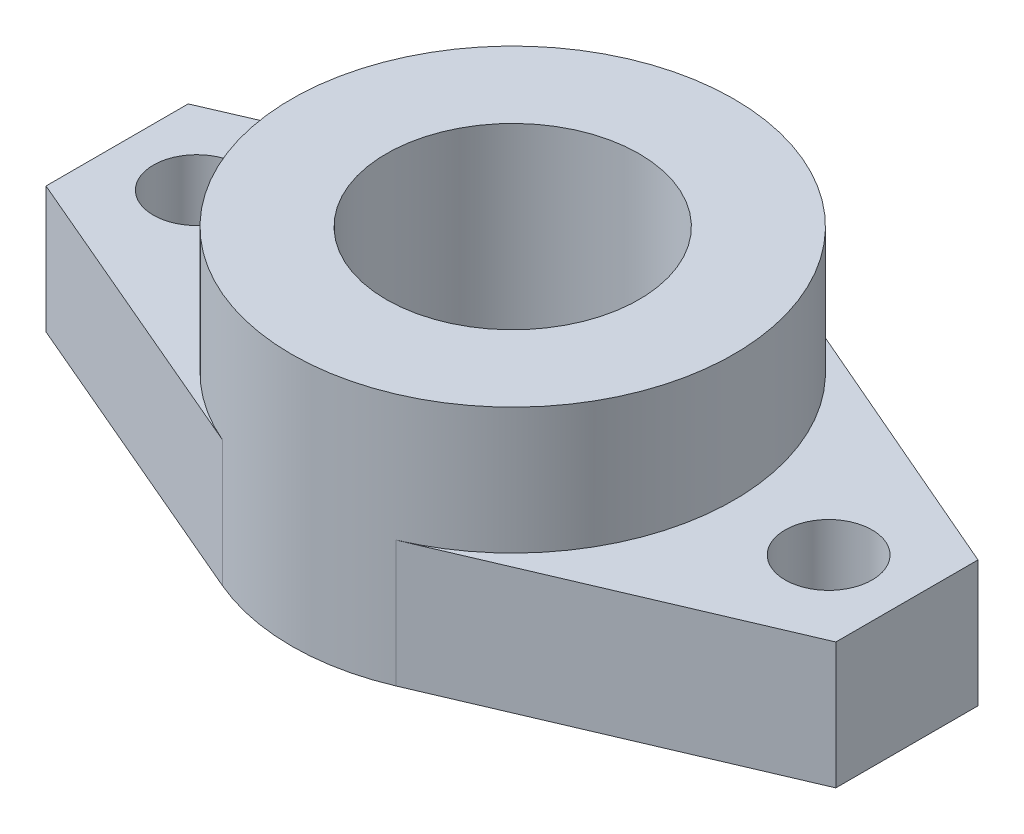
SolidWorks part; units mm, degrees
material "1060 合金"
ref_plane "前视基准面" through (0, 0, 0) normal (0, 0, 1) x (1, 0, 0)
ref_plane "上视基准面" through (0, 0, 0) normal (0, 1, 0) x (1, 0, 0)
ref_plane "右视基准面" through (0, 0, 0) normal (1, 0, 0) x (0, 0, -1)
sketch "草图1" plane through (0, 0, 0) normal (0, 1, 0) x (1, 0, 0)
  line L0 (20.1347, 0) -> (-18.5708, 0) construction
  line L1 (0, 0) -> (0, 18.2124) construction
  line L2 (-25, 4.4548) -> (-25, -4.5452)
  line L3 (25, 4.4548) -> (25, -4.5452)
  line L4 (-25, 4.4548) -> (-5.5497, 12.8531)
  line L5 (-25, -4.5452) -> (-5.4993, -12.8747)
  line L6 (25, -4.5452) -> (5.4993, -12.8747)
  line L7 (25, 4.4548) -> (5.5497, 12.8531)
  circle A0 centre (0, 0) radius 8
  arc A1 (-5.4993, -12.8747) -> (5.4993, -12.8747) centre (0, 0) ccw
  arc A2 (5.5497, 12.8531) -> (-5.5497, 12.8531) centre (0, 0) ccw
  dimension "D1" = 16
  dimension "D3" = 28
  dimension "D2" = 50
  dimension "D4" = 9
extrude "凸台-拉伸1" add sketch "草图1" along normal blind 8
sketch "草图2" plane through (0, 8, 0) normal (0, 1, 0) x (1, 0, 0)
  circle A0 centre (0, 0) radius 14
  circle A1 centre (0, 0) radius 8
  arc A2 (5.5497, 12.8531) -> (-5.5497, 12.8531) centre (0, 0) ccw construction
extrude "凸台-拉伸2" add sketch "草图2" along normal blind 8
hole_wizard "M5 间隙孔1" positions "草图4" profile "草图3" hole size "M5" standard "GB" end condition up to next
sketch "草图4" plane through (0, 8, 0) normal (0, 1, 0) x (1, 0, 0)
  line L2 (0, 0) -> (0, 18.8092) construction
  point P0 (-20, 0)
  point P16 (20, 0)
  dimension "D1" = 40
sketch "草图3" plane through (-20, 8, 0) normal (1, 0, 0) x (0, 0, 1)
  line L0 (0, 0) -> (0, 8)
  line L1 (0, 8) -> (2.75, 8)
  line L2 (2.75, 8) -> (2.75, 0)
  line L5 (2.75, 0) -> (0, 0)
  line L11 (0, -6.35) -> (0, 107.95) construction
  dimension "通孔孔直径" = 5.5
  dimension "通孔孔深度" = 8
